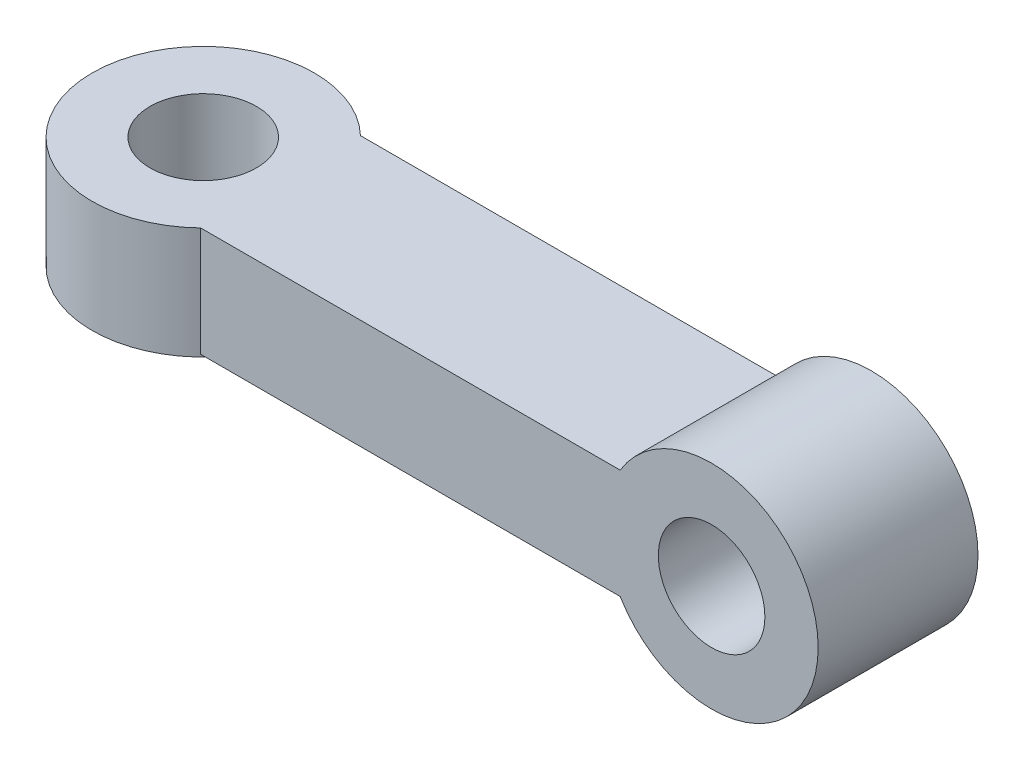
SolidWorks part; units mm, degrees
ref_plane "Front Plane" through (0, 0, 0) normal (0, 0, 1) x (1, 0, 0)
ref_plane "Top Plane" through (0, 0, 0) normal (0, 1, 0) x (1, 0, 0)
ref_plane "Right Plane" through (0, 0, 0) normal (1, 0, 0) x (0, 0, -1)
sketch "Sketch4" plane through (0, 0, 0) normal (0, 0, 1) x (1, 0, 0)
  line L0 (101.6892, -7.1452) -> (62.3192, -7.1452)
  line L1 (101.6892, 3.1254) -> (62.3192, 3.1254)
  line L2 (62.3192, -7.1452) -> (62.3192, 3.1254)
  arc A0 (101.6892, 3.1254) -> (101.6892, -7.1452) centre (110.2699, -2.0099) cw
  circle A1 centre (110.2699, -2.0099) radius 5
extrude "Boss-Extrude6" add sketch "Sketch4" along normal blind 15
sketch "Sketch9" plane through (0, 3.1254, 0) normal (0, 1, 0) x (1, 0, 0)
  circle A0 centre (55.064, -7.5) radius 10.4349
  circle A1 centre (55.064, -7.5) radius 5
extrude "Boss-Extrude8" add sketch "Sketch9" against normal blind 10.5
sketch "Sketch10" plane through (0, -7.1452, 0) normal (0, -1, 0) x (1, 0, 0)
  line L0 (110.2699, 15) -> (110.2699, 0) construction
  line L1 (115.2699, 15) -> (105.2699, 15) construction
  line L2 (101.6892, 0) -> (120.2699, 0) construction
  line L3 (55.064, 7.5) -> (110.2699, 7.5) construction
